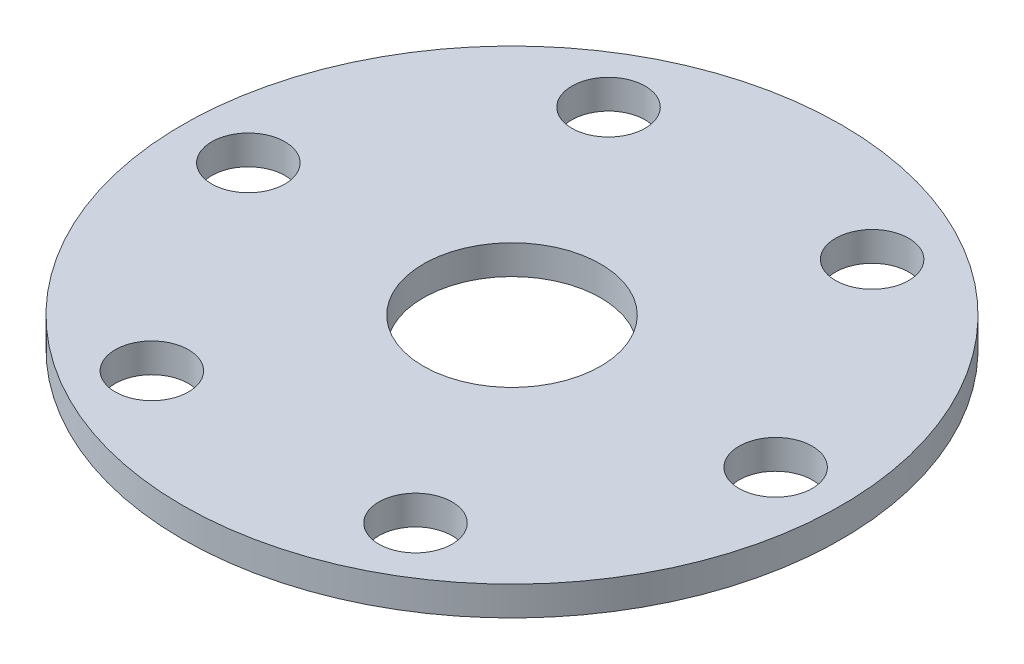
SolidWorks part; units mm, degrees
ref_plane "Front Plane" through (0, 0, 0) normal (0, 0, 1) x (1, 0, 0)
ref_plane "Top Plane" through (0, 0, 0) normal (0, 1, 0) x (1, 0, 0)
ref_plane "Right Plane" through (0, 0, 0) normal (1, 0, 0) x (0, 0, -1)
sketch "Sketch2" plane through (0, 0, 0) normal (0, 1, 0) x (1, 0, 0)
  line L0 (0, 0) -> (-18, 0) construction
  circle A0 centre (-18, 0) radius 2.5
  circle A1 centre (-9, 15.5885) radius 2.5
  circle A2 centre (9, 15.5885) radius 2.5
  circle A3 centre (18, 0) radius 2.5
  circle A4 centre (9, -15.5885) radius 2.5
  circle A5 centre (-9, -15.5885) radius 2.5
  circle A6 centre (0, 0) radius 22.5
  point P16 (0, 0)
  dimension "D2" = 5
  dimension "D4" = 45
  dimension "D1" = 18
  dimension "D3" = 6
extrude "Boss-Extrude1" add sketch "Sketch2" along normal blind 2
sketch "Sketch3" plane through (0, 2, 0) normal (0, 1, 0) x (1, 0, 0)
  circle A0 centre (0, 0) radius 6.05
  dimension "D1" = 12.1
extrude "Cut-Extrude1" cut sketch "Sketch3" against normal up to next
